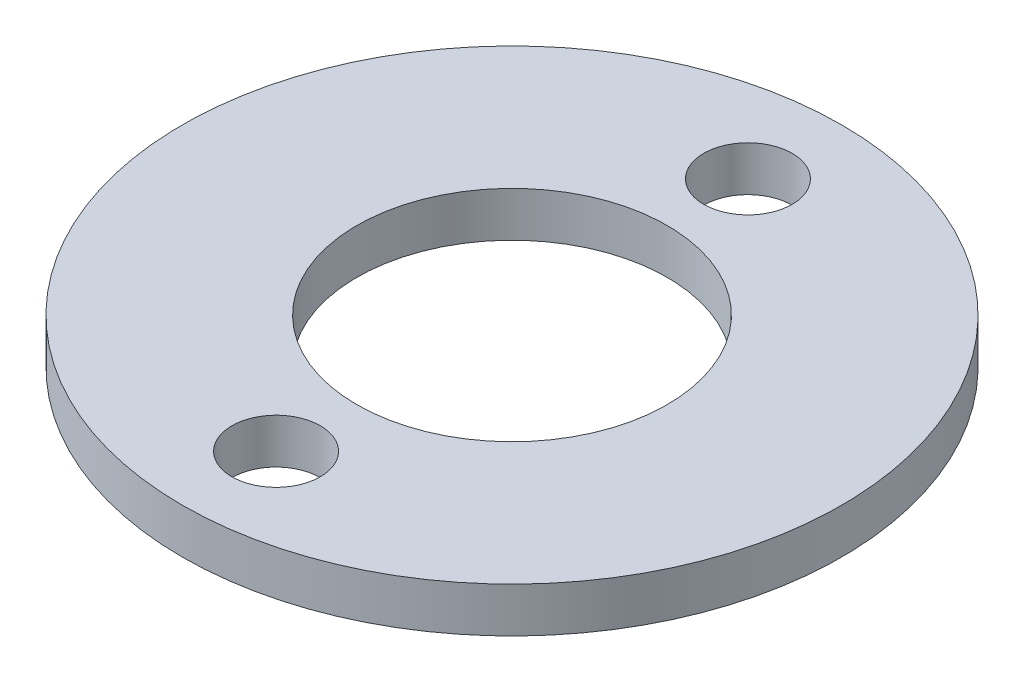
SolidWorks part; units mm, degrees
material "Alloy Steel"
ref_plane "Front Plane" through (0, 0, 0) normal (0, 0, 1) x (1, 0, 0)
ref_plane "Top Plane" through (0, 0, 0) normal (0, 1, 0) x (1, 0, 0)
ref_plane "Right Plane" through (0, 0, 0) normal (1, 0, 0) x (0, 0, -1)
sketch "Sketch1" plane through (0, 0, 0) normal (0, 1, 0) x (1, 0, 0)
  circle A0 centre (0, 0) radius 22
  dimension "D1" = 44
extrude "Boss-Extrude1" add sketch "Sketch1" along normal blind 3
sketch "Sketch2" plane through (0, 3, 0) normal (0, 1, 0) x (1, 0, 0)
  line L0 (-23.0208, 0) -> (24.8648, 0) construction
  circle A0 centre (0, 0) radius 10.36
  circle A1 centre (0, 15.75) radius 2.952
  circle A2 centre (0, -15.75) radius 2.952
  dimension "D1" = 20.72
  dimension "D2" = 5.904
  dimension "D3" = 15.75
extrude "Cut-Extrude1" cut sketch "Sketch2" against normal blind 3
